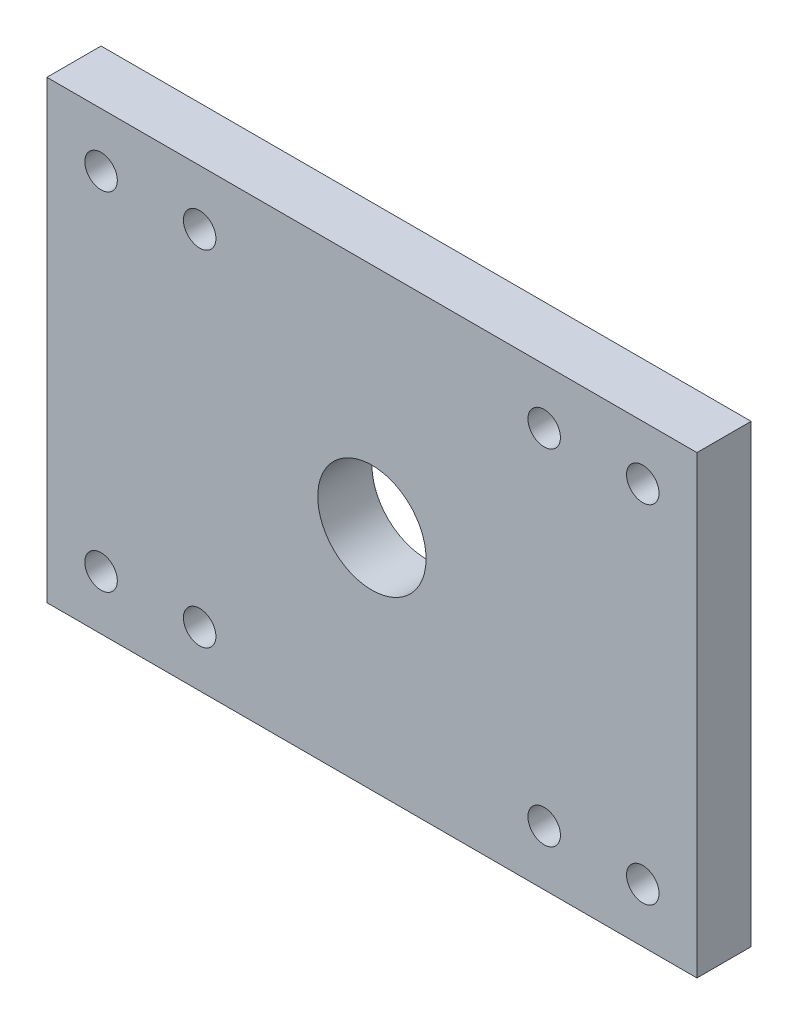
SolidWorks part; units mm, degrees
ref_plane "Front Plane" through (0, 0, 0) normal (0, 0, 1) x (1, 0, 0)
ref_plane "Top Plane" through (0, 0, 0) normal (0, 1, 0) x (1, 0, 0)
ref_plane "Right Plane" through (0, 0, 0) normal (1, 0, 0) x (0, 0, -1)
sketch "Sketch1" plane through (0, 0, 0) normal (0, 0, 1) x (1, 0, 0)
  line L1 (-30, 21) -> (30, 21)
  line L2 (-30, 21) -> (-30, -21)
  line L3 (-30, -21) -> (30, -21)
  line L4 (30, 21) -> (30, -21)
  line L5 (-30, 21) -> (30, -21) construction
  line L6 (-30, -21) -> (30, 21) construction
  line L7 (-15.9, 15.9) -> (15.9, 15.9)
  line L8 (-15.9, 15.9) -> (-15.9, -15.9)
  line L9 (-15.9, -15.9) -> (15.9, -15.9)
  line L10 (15.9, 15.9) -> (15.9, -15.9)
  line L11 (-15.9, 15.9) -> (15.9, -15.9) construction
  line L12 (-15.9, -15.9) -> (15.9, 15.9) construction
  line L13 (-25, -16) -> (25, -16)
  line L14 (-25, -16) -> (-25, 16)
  line L15 (-25, 16) -> (25, 16)
  line L16 (25, -16) -> (25, 16)
  line L17 (-25, -16) -> (25, 16) construction
  line L18 (-25, 16) -> (25, -16) construction
  circle A0 centre (-15.9, 15.9) radius 1.5
  circle A1 centre (15.9, 15.9) radius 1.5
  circle A2 centre (15.9, -15.9) radius 1.5
  circle A3 centre (-15.9, -15.9) radius 1.5
  circle A4 centre (-25, 16) radius 1.5
  circle A8 centre (0, 0) radius 5
  circle A9 centre (25, 16) radius 1.5
  circle A10 centre (25, -16) radius 1.5
  circle A11 centre (-25, -16) radius 1.5
  point P0 (0, 0)
  point P6 (0, 0)
  point P12 (0, 0)
  point P21 (0, 0)
  point P34 (4.5, -4.5)
  dimension "D1" = 4
extrude "Boss-Extrude1" add sketch "Sketch1" along normal blind 5
sketch "Sketch3" plane through (0, 0, 0) normal (0, 0, -1) x (-1, 0, 0)
  circle A0 centre (-15.9, 15.9) radius 2.625
  circle A1 centre (15.9, 15.9) radius 2.625
  circle A2 centre (15.9, -15.9) radius 2.625
  circle A3 centre (-15.9, -15.9) radius 2.625
  point P12 (0, 0)
  dimension "D1" = 4
extrude "Cut-Extrude4" cut sketch "Sketch3" against normal blind 2.5
